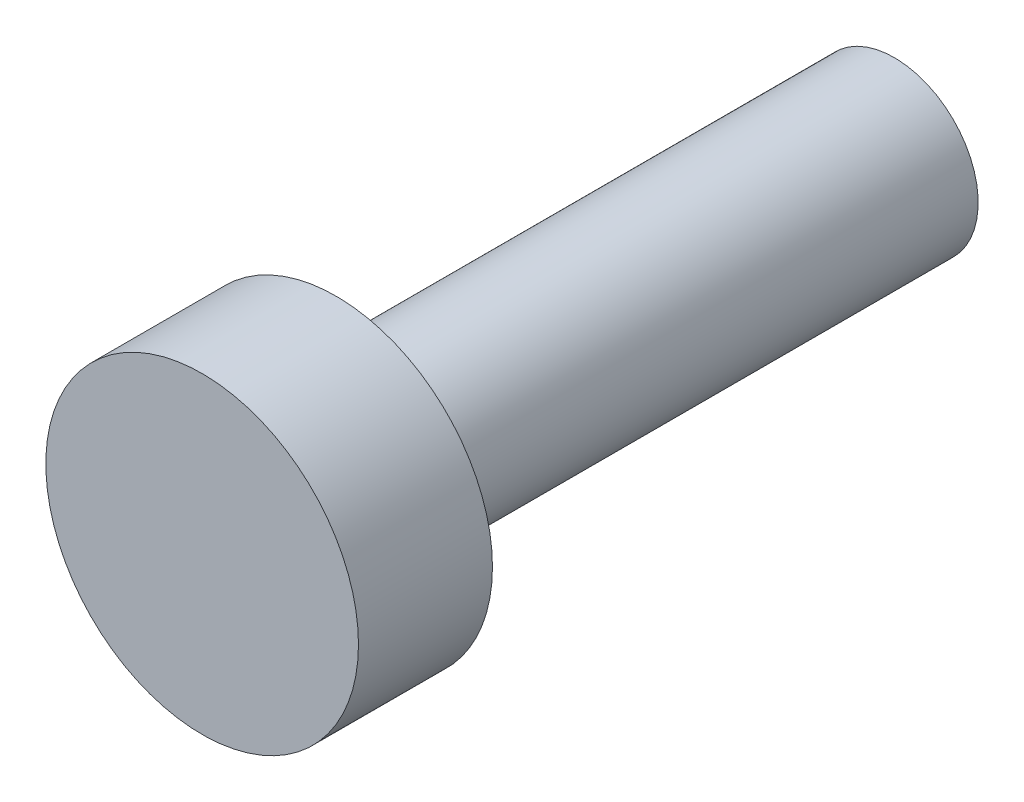
SolidWorks part; units mm, degrees
ref_plane "Plan de face" through (0, 0, 0) normal (0, 0, 1) x (1, 0, 0)
ref_plane "Plan de dessus" through (0, 0, 0) normal (0, 1, 0) x (1, 0, 0)
ref_plane "Plan de droite" through (0, 0, 0) normal (1, 0, 0) x (0, 0, -1)
sketch "Esquisse1" plane through (0, 0, 0) normal (0, 0, 1) x (1, 0, 0)
  circle A0 centre (0, 0) radius 2.8
  dimension "D1" = 5.6
extrude "Boss.-Extru.1" add sketch "Esquisse1" along normal blind 2.4
sketch "Esquisse2" plane through (0, 0, 0) normal (0, 0, -1) x (-1, 0, 0)
  circle A0 centre (0, 0) radius 1.5
  dimension "D1" = 3
extrude "Boss.-Extru.2" add sketch "Esquisse2" along normal blind 10
